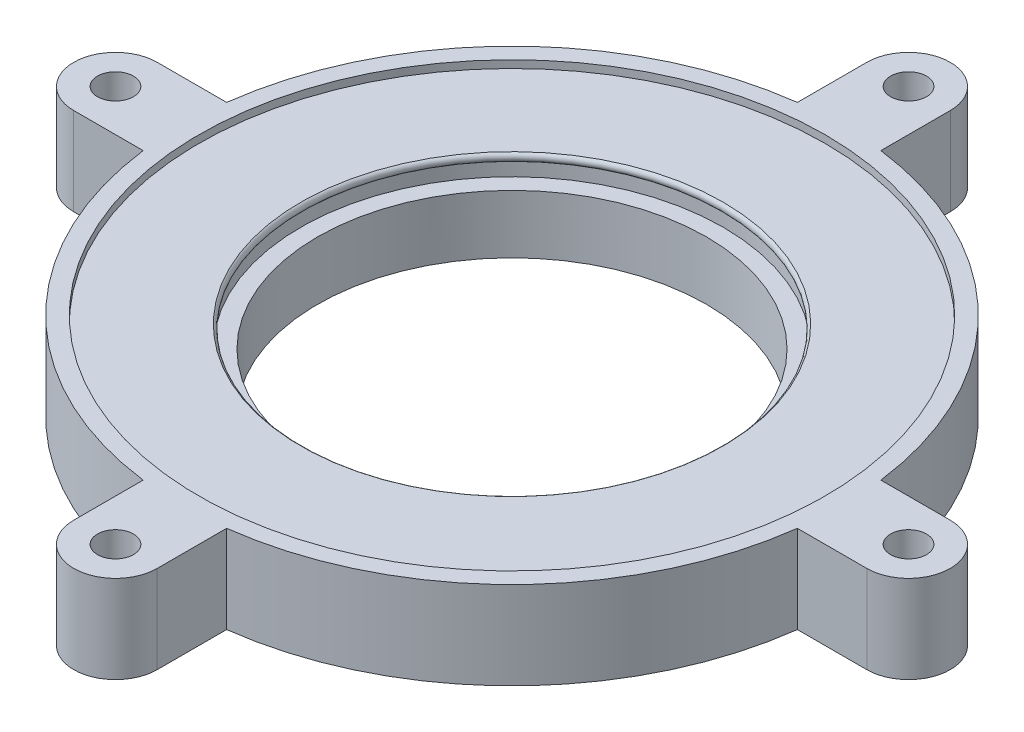
SolidWorks part; units mm, degrees
ref_plane "Front Plane" through (0, 0, 0) normal (0, 0, 1) x (1, 0, 0)
ref_plane "Top Plane" through (0, 0, 0) normal (0, 1, 0) x (1, 0, 0)
ref_plane "Right Plane" through (0, 0, 0) normal (1, 0, 0) x (0, 0, -1)
sketch "Sketch1" plane through (0, 0, 0) normal (1, 0, 0) x (0, 0, -1)
  line L0 (-37.5, -1.0482) -> (-37.5, -1.9554)
  line L1 (-37.5, -1.9554) -> (-25.3, -1.9554)
  line L2 (-25.3, -2.9554) -> (-25.3, -4.5554)
  line L3 (-25.3, -4.5554) -> (-8, -4.5554)
  line L4 (-8, -4.5554) -> (-8, -11.5554)
  line L5 (-8, -11.5554) -> (-39.5, -11.5554)
  line L6 (-39.5, -11.5554) -> (-39.5, -1.0482)
  line L9 (-39.5, -1.0482) -> (-37.5, -1.0482)
  line L10 (0, -1000) -> (0, 49000) construction
  arc A0 (-25.3, -1.9554) -> (-25.3, -2.9554) centre (-25.5667, -2.4554) cw
  point P13 (-25, -2.4554)
  point P17 (-37.5, -1.5018)
  dimension "D2" = 1.6
  dimension "D4" = 1
  dimension "D1" = 25.3
  dimension "D3" = 0.3
  dimension "D5" = 37.5
  dimension "D6" = 7
  dimension "D7" = 2
  dimension "D8" = 8
revolve "Revolve1" add sketch "Sketch1" angle 360 about L10
sketch "Sketch2" plane through (0, -11.5554, 0) normal (0, -1, 0) x (1, 0, 0)
  line L0 (0, 0) -> (0, 47.5) construction
  line L1 (-5, 47.5) -> (-5, 39.1823)
  line L2 (5, 47.5) -> (5, 39.1823)
  line L3 (5, 39.1823) -> (-5, 39.1823)
  line L4 (47.5, -5) -> (39.1823, -5)
  line L5 (47.5, 5) -> (39.1823, 5)
  line L6 (39.1823, -5) -> (39.1823, 5)
  line L7 (-5, -47.5) -> (-5, -39.1823)
  line L8 (5, -47.5) -> (5, -39.1823)
  line L9 (-5, -39.1823) -> (5, -39.1823)
  line L10 (-47.5, 5) -> (-39.1823, 5)
  line L11 (-47.5, -5) -> (-39.1823, -5)
  line L12 (-39.1823, 5) -> (-39.1823, -5)
  circle A0 centre (0, 47.5) radius 2.15
  arc A1 (5, 47.5) -> (-5, 47.5) centre (0, 47.5) ccw
  circle A2 centre (0, 0) radius 39.5 construction
  arc A3 (47.5, -5) -> (47.5, 5) centre (47.5, 0) ccw
  arc A4 (-5, -47.5) -> (5, -47.5) centre (0, -47.5) ccw
  arc A5 (-47.5, 5) -> (-47.5, -5) centre (-47.5, 0) ccw
  circle A6 centre (47.5, 0) radius 2.15
  circle A7 centre (0, -47.5) radius 2.15
  circle A8 centre (-47.5, 0) radius 2.15
  point P28 (0, 0)
  dimension "D2" = 4.3
  dimension "D3" = 10
  dimension "D1" = 47.5
  dimension "D4" = 4
extrude "Boss-Extrude1" add sketch "Sketch2" against normal up to surface (10.5072 mm away) up to face at (0, -1.0482, -37.5)
sketch "Sketch3" plane through (0, -4.5554, 0) normal (0, 1, 0) x (1, 0, 0)
  line L0 (0, 0) -> (50000, 0) construction
  line L1 (21.9383, -2) -> (12.3693, -2)
  line L2 (2, -12.3693) -> (2, -21.9383)
  line L3 (0, -0.3712) -> (0, -50000.3712) construction
  line L4 (-2, -21.9383) -> (-2, -12.3693)
  line L5 (-12.3693, -2) -> (-21.9383, -2)
  line L6 (-21.9383, 2) -> (-12.3693, 2)
  line L7 (-2, 12.3693) -> (-2, 21.9383)
  line L8 (2, 21.9383) -> (2, 12.3693)
  line L9 (12.3693, 2) -> (21.9383, 2)
  arc A1 (3.3846, -10.4663) -> (10.4663, -3.3846) centre (0, 0) ccw
  circle A2 centre (0, 0) radius 8 construction
  arc A4 (4.3587, -23.9059) -> (23.9059, -4.3587) centre (0, 0) ccw
  arc A5 (2, -12.3693) -> (3.3846, -10.4663) centre (4, -12.3693) cw
  arc A6 (2, -21.9383) -> (4.3587, -23.9059) centre (4, -21.9383) ccw
  arc A7 (21.9383, -2) -> (23.9059, -4.3587) centre (21.9383, -4) cw
  arc A8 (12.3693, -2) -> (10.4663, -3.3846) centre (12.3693, -4) ccw
  arc A9 (-23.9059, -4.3587) -> (-4.3587, -23.9059) centre (0, 0) ccw
  arc A10 (-2, -21.9383) -> (-4.3587, -23.9059) centre (-4, -21.9383) cw
  arc A11 (-2, -12.3693) -> (-3.3846, -10.4663) centre (-4, -12.3693) ccw
  arc A12 (-10.4663, -3.3846) -> (-3.3846, -10.4663) centre (0, 0) ccw
  arc A13 (-12.3693, -2) -> (-10.4663, -3.3846) centre (-12.3693, -4) cw
  arc A14 (-21.9383, -2) -> (-23.9059, -4.3587) centre (-21.9383, -4) ccw
  arc A15 (-4.3587, 23.9059) -> (-23.9059, 4.3587) centre (0, 0) ccw
  arc A16 (-21.9383, 2) -> (-23.9059, 4.3587) centre (-21.9383, 4) cw
  arc A17 (-12.3693, 2) -> (-10.4663, 3.3846) centre (-12.3693, 4) ccw
  arc A18 (-3.3846, 10.4663) -> (-10.4663, 3.3846) centre (0, 0) ccw
  arc A19 (-2, 12.3693) -> (-3.3846, 10.4663) centre (-4, 12.3693) cw
  arc A20 (-2, 21.9383) -> (-4.3587, 23.9059) centre (-4, 21.9383) ccw
  arc A21 (23.9059, 4.3587) -> (4.3587, 23.9059) centre (0, 0) ccw
  arc A22 (2, 21.9383) -> (4.3587, 23.9059) centre (4, 21.9383) cw
  arc A23 (2, 12.3693) -> (3.3846, 10.4663) centre (4, 12.3693) ccw
  arc A24 (10.4663, 3.3846) -> (3.3846, 10.4663) centre (0, 0) ccw
  arc A25 (12.3693, 2) -> (10.4663, 3.3846) centre (12.3693, 4) cw
  arc A26 (21.9383, 2) -> (23.9059, 4.3587) centre (21.9383, 4) ccw
  point P59 (0, 0)
  dimension "D2" = 2
  dimension "D1" = 3
  dimension "D3" = 2
  dimension "D4" = 2
  dimension "D5" = 4
extrude "Cut-Extrude2" cut sketch "Sketch3" against normal up to surface (7 mm away) up to face at (0, -11.5554, 0)
sketch "Sketch4" plane through (0, -11.5554, 0) normal (0, -1, 0) x (-1, 0, 0)
  line L0 (0, 0) -> (30, 0) construction
  line L1 (0, 0) -> (50000, 0) construction
  circle A0 centre (30, 0) radius 2.15
  circle A1 centre (0, -30) radius 2.15
  circle A2 centre (-30, 0) radius 2.15
  circle A3 centre (0, 30) radius 2.15
  point P15 (0, 0)
  dimension "D3" = 4.3
  dimension "D1" = 0
  dimension "D2" = 30
  dimension "D4" = 4
extrude "Cut-Extrude3" cut sketch "Sketch4" against normal blind 7
sketch "Sketch5" plane through (0, -11.5554, 0) normal (0, -1, 0) x (1, 0, 0)
  circle A0 centre (0, 0) radius 23.3
  circle A1 centre (0, 0) radius 24.3
  arc A2 (-4.3587, 23.9059) -> (-23.9059, 4.3587) centre (0, 0) ccw construction
  dimension "D1" = 1
extrude "Boss-Extrude2" add sketch "Sketch5" against normal up to surface (7 mm away) up to face at (10.4854, -4.5554, -10.4854)
sketch "Sketch6" plane through (0, -4.5554, 0) normal (0, 1, 0) x (1, 0, 0)
  circle A0 centre (0, 0) radius 23.3
extrude "Cut-Extrude4" cut sketch "Sketch6" against normal through all
equation "\"D4@Sketch3\"=\"D3@Sketch3\""
